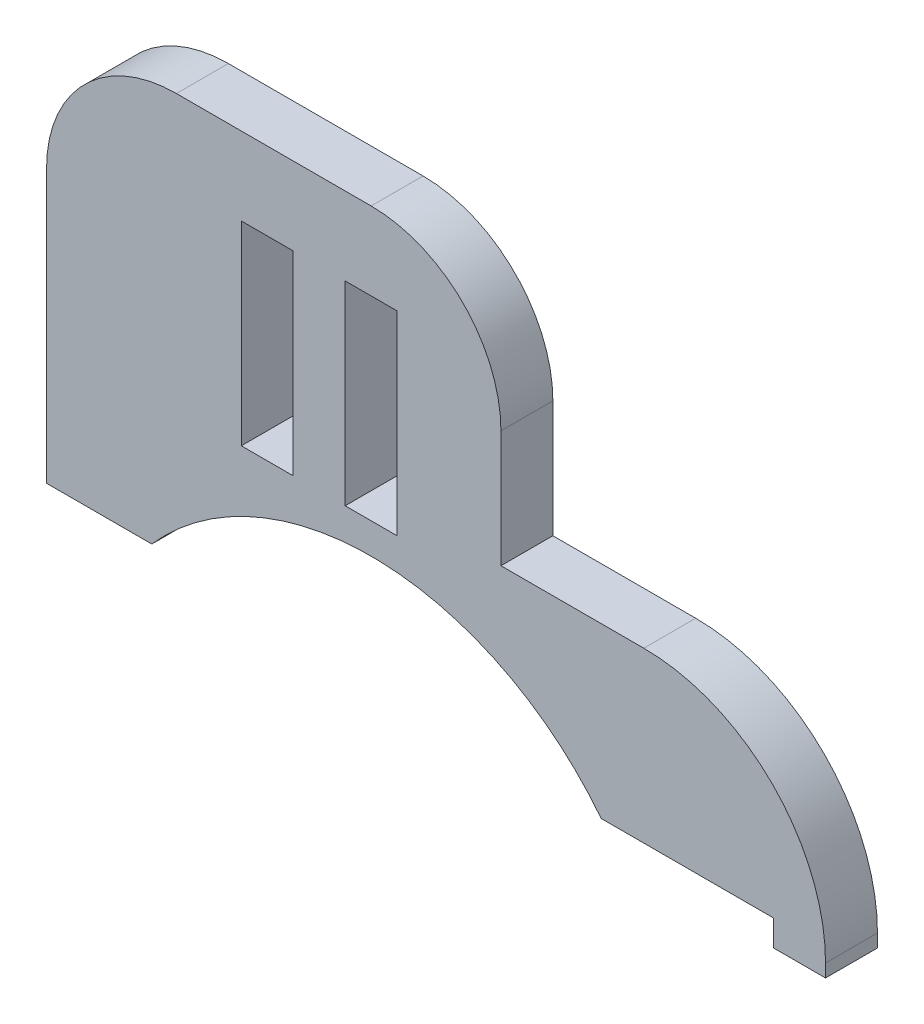
SolidWorks part; units mm, degrees
ref_plane "Front Plane" through (0, 0, 0) normal (0, 0, 1) x (1, 0, 0)
ref_plane "Top Plane" through (0, 0, 0) normal (0, 1, 0) x (1, 0, 0)
ref_plane "Right Plane" through (0, 0, 0) normal (1, 0, 0) x (0, 0, -1)
sketch "Sketch1" plane through (0, 0, 0) normal (0, 0, 1) x (1, 0, 0)
  line L1 (-38.1, -7.62) -> (38.1, -7.62)
  line L2 (-38.1, -7.62) -> (-38.1, 7.62)
  line L3 (-38.1, 7.62) -> (38.1, 7.62)
  line L4 (38.1, -7.62) -> (38.1, 7.62)
  line L5 (-38.1, -7.62) -> (38.1, 7.62) construction
  line L6 (-38.1, 7.62) -> (38.1, -7.62) construction
  point P0 (0, 0)
  dimension "D1" = 15.24
  dimension "D2" = 76.2
extrude "Boss-Extrude1" add sketch "Sketch1" along normal blind 5.08
sketch "Sketch2" plane through (0, 0, 0) normal (0, 1, 0) x (1, 0, 0)
  line L0 (6.35, 0) -> (0, 0) construction
  line L2 (-19.05, 0) -> (6.35, 0)
  line L3 (-19.05, 0) -> (-19.05, -5.08)
  line L4 (-19.05, -5.08) -> (6.35, -5.08)
  line L5 (6.35, 0) -> (6.35, -5.08)
  line L6 (-19.05, 0) -> (6.35, -5.08) construction
  line L7 (-19.05, -5.08) -> (6.35, 0) construction
  point P0 (-37.9754, 0)
  point P4 (-6.35, -2.54)
  dimension "D1" = 5.08
  dimension "D2" = 25.4
  dimension "D3" = 6.35
extrude "Boss-Extrude2" add sketch "Sketch2" along normal blind 31.75
sketch "Sketch4" plane through (0, 0, 0) normal (0, 0, -1) x (-1, 0, 0)
  line L0 (3.81, 24.13) -> (3.81, 31.75) construction
  line L1 (19.05, 31.75) -> (-6.35, 31.75) construction
  line L2 (19.05, 31.75) -> (19.05, 14.605) construction
  line L3 (19.05, 14.605) -> (-6.35, 14.605) construction
  line L4 (-6.35, 31.75) -> (-6.35, 14.605) construction
  line L5 (8.89, 24.13) -> (3.81, 24.13)
  line L6 (8.89, 24.13) -> (8.89, 5.08)
  line L7 (8.89, 5.08) -> (3.81, 5.08)
  line L8 (3.81, 24.13) -> (3.81, 5.08)
  line L9 (8.89, 24.13) -> (3.81, 5.08) construction
  line L10 (8.89, 5.08) -> (3.81, 24.13) construction
  line L11 (3.81, 24.13) -> (-6.35, 24.13) construction
  line L12 (8.89, 24.13) -> (19.05, 24.13) construction
  point P6 (6.35, 14.605)
  point P13 (6.35, 14.605)
  dimension "D1" = 5.08
  dimension "D2" = 19.05
  dimension "D3" = 7.62
extrude "Cut-Extrude2" cut sketch "Sketch4" against normal blind 50.8
sketch "Sketch6" plane through (-19.05, 0, 0) normal (-1, 0, 0) x (0, 0, 1)
  line L1 (0, 31.75) -> (5.08, 31.75)
  line L2 (0, 31.75) -> (0, -2.54)
  line L3 (0, -2.54) -> (5.08, -2.54)
  line L4 (5.08, 31.75) -> (5.08, -2.54)
  dimension "D2" = 5.08
  dimension "D1" = 34.29
extrude "Boss-Extrude3" add sketch "Sketch6" along normal blind 19.05
sketch "Sketch7" plane through (0, 0, 0) normal (0, 0, -1) x (-1, 0, 0)
  line L0 (8.89, 5.08) -> (13.97, 5.08) construction
  line L1 (13.97, 5.08) -> (13.97, 24.13) construction
  line L2 (13.97, 24.13) -> (8.89, 24.13) construction
  line L4 (13.97, 5.08) -> (19.05, 5.08)
  line L5 (13.97, 5.08) -> (13.97, 24.13)
  line L6 (13.97, 24.13) -> (19.05, 24.13)
  line L7 (19.05, 5.08) -> (19.05, 24.13)
  dimension "D1" = 5.08
  dimension "D2" = 5.08
extrude "Cut-Extrude4" cut sketch "Sketch7" against normal blind 19.05
fillet "Fillet1" radius 12.7 2 edges at (6.35, 31.75, 2.54) (-38.1, 31.75, 2.54)
sketch "Sketch12" plane through (0, -7.62, 0) normal (0, -1, 0) x (1, 0, 0)
  line L0 (-38.1, 5.08) -> (38.1, 5.08) construction
  line L1 (38.1, 0) -> (33.02, 0)
  line L2 (38.1, 0) -> (38.1, 5.08)
  line L3 (38.1, 5.08) -> (33.02, 5.08)
  line L4 (33.02, 0) -> (33.02, 5.08)
  dimension "D1" = 5.08
extrude "Boss-Extrude5" add sketch "Sketch12" along normal blind 3.81
sketch "Sketch14" plane through (0, -7.62, 0) normal (0, -1, 0) x (1, 0, 0)
  line L0 (-38.1, 0) -> (33.02, 0) construction
  line L1 (33.02, 5.08) -> (1.5797, 5.08)
  line L2 (33.02, 5.08) -> (33.02, 0)
  line L3 (33.02, 0) -> (1.5797, 0)
  line L4 (1.5797, 5.08) -> (1.5797, 0)
extrude "Boss-Extrude7" add sketch "Sketch14" along normal blind 1.27
sketch "Sketch9" plane through (0, 0, 5.08) normal (0, 0, 1) x (1, 0, 0)
  line L1 (-3.81, 5.08) -> (-8.89, 5.08) construction
  line L2 (-6.35, 5.08) -> (-6.35, 2.08) construction
  line L3 (-6.35, 2.08) -> (-6.35, -26.495) construction
  line L6 (22.0483, -23.3224) -> (-34.7483, -23.3224)
  arc A0 (-34.7483, -23.3224) -> (-6.35, 2.08) centre (-6.35, -26.495) cw
  arc A1 (-6.35, 2.08) -> (22.0483, -23.3224) centre (-6.35, -26.495) cw
  point P4 (-6.35, 5.08)
  dimension "D1" = 3
  dimension "D2" = 28.575
extrude "Cut-Extrude7" cut sketch "Sketch9" against normal through all
fillet "Fillet3" radius 17.78 1 edges at (38.1, 7.62, 2.54)
equation "\"Foamcore\" = .1in"
equation "\"MDF\" = .2in"
equation "\"Gmaterial\"= \"MDF\""
equation "\"PVC-ID\" = \"1.590in\""
equation "\"PVC-OD\" = \"1.900in\""
equation "\"PVC-Sleeve-Width\" = \".51in\""
equation "\"D1@Boss-Extrude1\"=\"Gmaterial\""
equation "\"D1@Sketch4\"=\"Gmaterial\""
equation "\"D2@Sketch7\"=\"Gmaterial\""
equation "\"D1@Sketch7\"=\"Gmaterial\""
equation "\"D1@Sketch2\"=\"Gmaterial\""
equation "\"D2@Sketch6\"=\"Gmaterial\""
equation "\"D1@Sketch1\"=.6"
